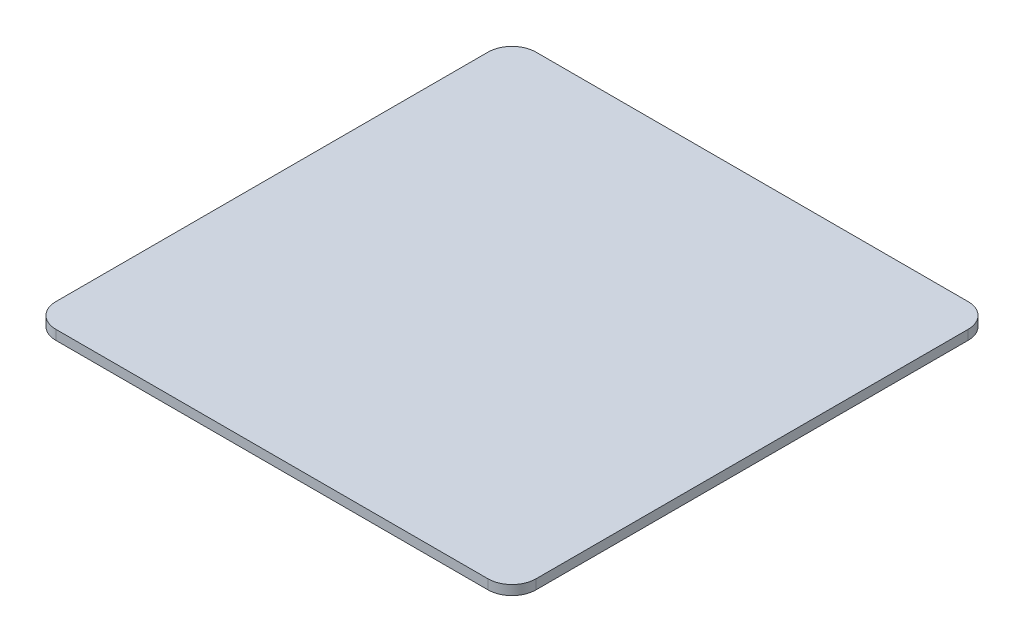
SolidWorks part; units mm, degrees
ref_plane "Front Plane" through (0, 0, 0) normal (0, 0, 1) x (1, 0, 0)
ref_plane "Top Plane" through (0, 0, 0) normal (0, 1, 0) x (1, 0, 0)
ref_plane "Right Plane" through (0, 0, 0) normal (1, 0, 0) x (0, 0, -1)
sketch "Sketch1" plane through (0, 0, 0) normal (0, 1, 0) x (1, 0, 0)
  line L1 (-25, -25) -> (25, -25)
  line L2 (-25, -25) -> (-25, 25)
  line L3 (-25, 25) -> (25, 25)
  line L4 (25, -25) -> (25, 25)
  line L5 (-25, -25) -> (25, 25) construction
  line L6 (-25, 25) -> (25, -25) construction
  point P0 (0, 0)
  dimension "D1" = 50
extrude "Boss-Extrude1" add sketch "Sketch1" along normal blind 1
fillet "Fillet1" radius 2.5 4 edges at (-25, 0.5, -25) (25, 0.5, -25) (25, 0.5, 25) (-25, 0.5, 25)
